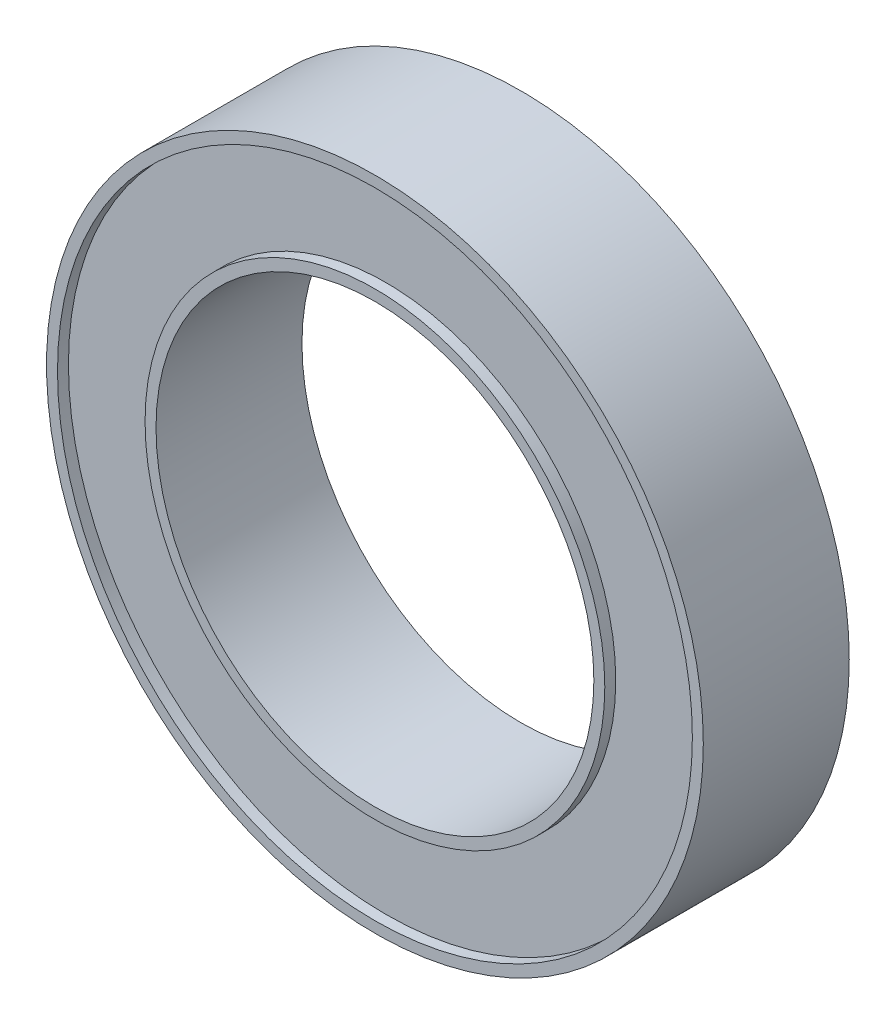
SolidWorks part; units mm, degrees
ref_plane "前视基准面" through (0, 0, 0) normal (0, 0, 1) x (1, 0, 0)
ref_plane "上视基准面" through (0, 0, 0) normal (0, 1, 0) x (1, 0, 0)
ref_plane "右视基准面" through (0, 0, 0) normal (1, 0, 0) x (0, 0, -1)
sketch "草图1" plane through (0, 0, 0) normal (0, 0, 1) x (1, 0, 0)
  circle A1 centre (0, 0) radius 9
  circle A2 centre (0, 0) radius 6
  dimension "D1" = 18
  dimension "D2" = 12
extrude "凸台-拉伸1" add sketch "草图1" along normal mid plane 4
sketch "草图2" plane through (0, 0, 2) normal (0, 0, 1) x (1, 0, 0)
  circle A5 centre (0, 0) radius 8.7
  circle A6 centre (0, 0) radius 8.7
  circle A8 centre (0, 0) radius 6.3
  circle A9 centre (0, 0) radius 6.3
  dimension "D1" = 0.3
  dimension "D2" = 0.3
extrude "切除-拉伸1" cut sketch "草图2" against normal blind 0.3
mirror "镜向1" about plane through (0, 0, 0) normal (0, 0, 1) of "切除-拉伸1"
